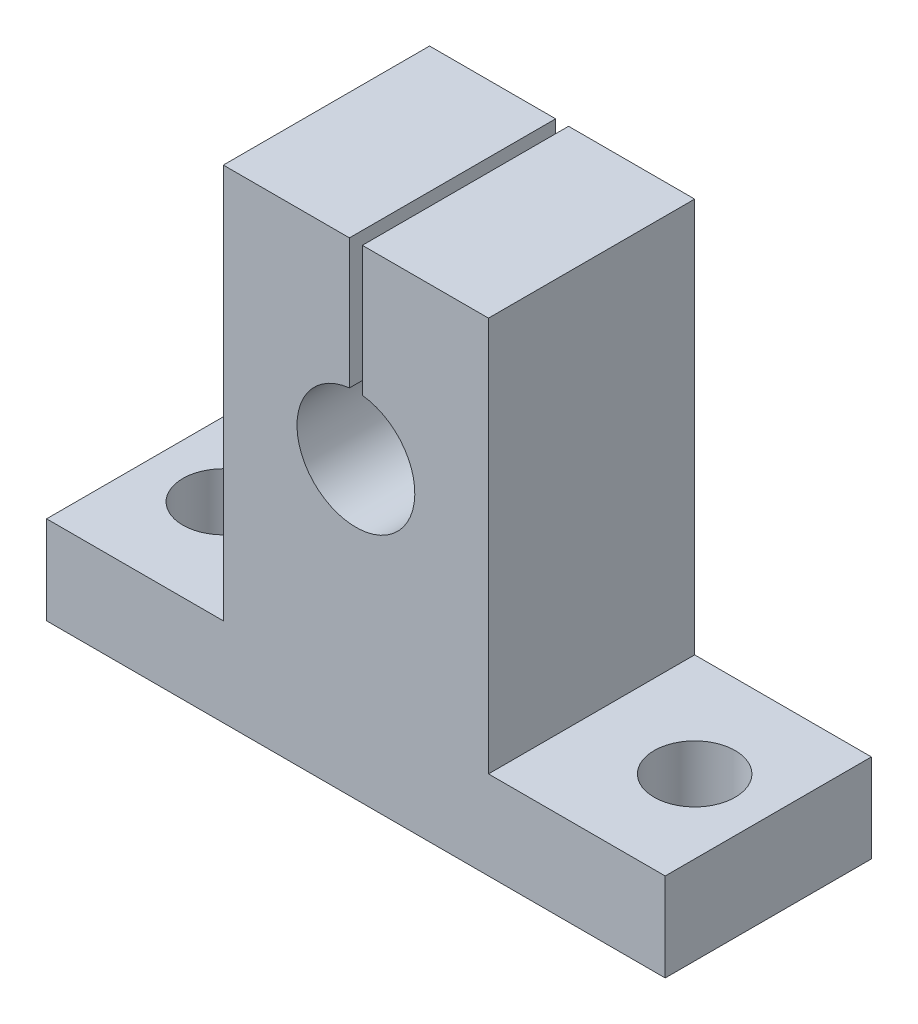
SolidWorks part; units mm, degrees
ref_plane "前视基准面" through (0, 0, 0) normal (0, 0, 1) x (1, 0, 0)
ref_plane "上视基准面" through (0, 0, 0) normal (0, 1, 0) x (1, 0, 0)
ref_plane "右视基准面" through (0, 0, 0) normal (1, 0, 0) x (0, 0, -1)
sketch "草图1" plane through (0, 0, 0) normal (0, 0, 1) x (1, 0, 0)
  line L0 (21, -20) -> (-21, -20)
  line L1 (-21, -20) -> (-21, -14)
  line L2 (-21, -14) -> (-9, -14)
  line L3 (-9, -14) -> (-9, 12.8)
  line L4 (-9, 12.8) -> (-0.4388, 12.8)
  line L6 (-0.4388, 12.8) -> (-0.4388, 3.9759)
  line L7 (21, -20) -> (21, -14)
  line L8 (21, -14) -> (9, -14)
  line L9 (9, -14) -> (9, 12.8)
  line L10 (0.4388, 12.8) -> (0.4388, 3.9759)
  line L11 (0.4388, 12.8) -> (9, 12.8)
  arc A0 (-0.4388, 3.9759) -> (0.4388, 3.9759) centre (0, 0) ccw
  point P5 (-0.4388, 12.8)
  point P14 (0, -20)
  dimension "D1" = 21
  dimension "D2" = 6
  dimension "D4" = 26.8
  dimension "D5" = 20
extrude "凸台-拉伸2" add sketch "草图1" along normal blind 14
sketch "草图2" plane through (0, -14, 0) normal (0, 1, 0) x (1, 0, 0)
  line L0 (-9, -14) -> (-9, 0) construction
  line L1 (-9, 0) -> (-21, 0) construction
  line L4 (9, -14) -> (9, 0) construction
  line L5 (21, -14) -> (9, -14) construction
  circle A0 centre (-16, -7) radius 2.75
  circle A1 centre (16, -7) radius 2.75
  point P0 (-16, -7)
  point P7 (16, -7)
  dimension "D3" = 7
  dimension "D1" = 7
  dimension "D2" = 7
  dimension "D4" = 7
extrude "切除-拉伸1" cut sketch "草图2" against normal through all
